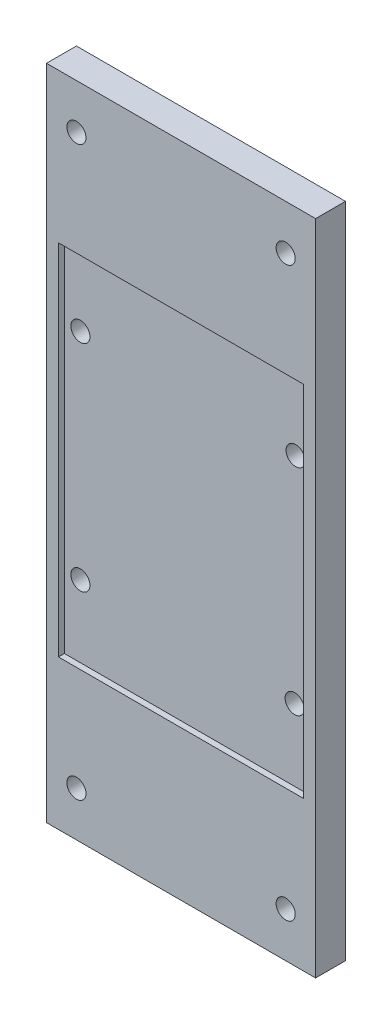
SolidWorks part; units mm, degrees
ref_plane "前视基准面" through (0, 0, 0) normal (0, 0, 1) x (1, 0, 0)
ref_plane "上视基准面" through (0, 0, 0) normal (0, 1, 0) x (1, 0, 0)
ref_plane "右视基准面" through (0, 0, 0) normal (1, 0, 0) x (0, 0, -1)
other "Configuration Table"
sketch "草图1" plane through (0, 0, 0) normal (0, 0, 1) x (1, 0, 0)
  line L1 (22.5, -50) -> (-22.5, -50)
  line L2 (22.5, -50) -> (22.5, 50)
  line L3 (22.5, 50) -> (-22.5, 50)
  line L4 (-22.5, -50) -> (-22.5, 50)
  line L5 (22.5, -50) -> (-22.5, 50) construction
  line L6 (22.5, 50) -> (-22.5, -50) construction
  point P0 (0, 0)
extrude "凸台-拉伸1" add sketch "草图1" along normal blind 5
sketch "草图2" plane through (0, 0, 5) normal (0, 0, 1) x (1, 0, 0)
  line L1 (20.5, -30) -> (-20.5, -30)
  line L2 (20.5, -30) -> (20.5, 30)
  line L3 (20.5, 30) -> (-20.5, 30)
  line L4 (-20.5, -30) -> (-20.5, 30)
  line L5 (20.5, -30) -> (-20.5, 30) construction
  line L6 (20.5, 30) -> (-20.5, -30) construction
  point P0 (0, 0)
extrude "切除-拉伸1" cut sketch "草图2" against normal blind 1
sketch "草图3" plane through (0, 0, 4) normal (0, 0, 1) x (1, 0, 0)
  line L0 (20.5, -18) -> (20.5, 18)
  line L1 (20.5, -30) -> (20.5, 30) construction
  line L2 (20.5, 18) -> (18.1665, 18)
  line L3 (20.5, -18) -> (18, -18)
  line L6 (-17.8335, 18) -> (-17.8335, -18)
  line L7 (-17.8335, 18) -> (18.1665, 18)
  circle A0 centre (18.1665, 18) radius 1.6
  circle A1 centre (18, -18) radius 1.6
  circle A2 centre (-17.8335, 18) radius 1.6
  circle A3 centre (-17.8335, -18) radius 1.6
  point P5 (20.5, 0)
  dimension "D1" = 3.2
  dimension "D2" = 3.2
  dimension "D3" = 3.2
  dimension "D4" = 3.2
sketch "草图4" plane through (0, 0, 5) normal (0, 0, 1) x (1, 0, 0)
  line L0 (17.5, 50) -> (-17.5, 50)
  line L1 (22.5, 50) -> (-22.5, 50) construction
  line L3 (17.5, -50) -> (-17.5, -50)
  line L4 (-22.5, -50) -> (22.5, -50) construction
  line L6 (-17.5, 47.5) -> (-17.5, -47.5)
  line L7 (17.5, 47.5) -> (17.5, -47.5)
  circle A0 centre (-17.5, 47.5) radius 1.6
  circle A1 centre (17.5, 47.5) radius 1.6
  circle A2 centre (-17.5, -47.5) radius 1.6
  circle A3 centre (17.5, -47.5) radius 1.6
  point P5 (0, 50)
  point P15 (0, -50)
  point P19 (-17.5, 0)
  point P22 (17.5, 0)
  dimension "D1" = 3.2
  dimension "D2" = 3.2
  dimension "D3" = 3.2
  dimension "D4" = 3.2
sketch "草图5" plane through (0, 0, 5) normal (0, 0, 1) x (1, 0, 0)
  line L0 (-22.5, 50) -> (22.5, 50)
  line L1 (22.5, 50) -> (22.5, 55)
  line L2 (22.5, 55) -> (-22.5, 55)
  line L3 (-22.5, 55) -> (-22.5, 50)
  line L4 (-22.5, -50) -> (22.5, -50)
  line L5 (-22.5, 50) -> (-22.5, -50) construction
  line L6 (-22.5, -50) -> (22.5, -50) construction
  line L7 (22.5, -50) -> (22.5, -55)
  line L8 (22.5, -55) -> (-22.5, -55)
  line L9 (-22.5, -55) -> (-22.5, -50)
extrude "凸台-拉伸2" add sketch "草图5" against normal blind 5
extrude "切除-拉伸4" cut sketch "草图4" against normal blind 10
extrude "切除-拉伸7" cut sketch "草图3" against normal blind 10 contours L7 A2 L6 | L6 A2 L7 | A3 | A1 | A0
